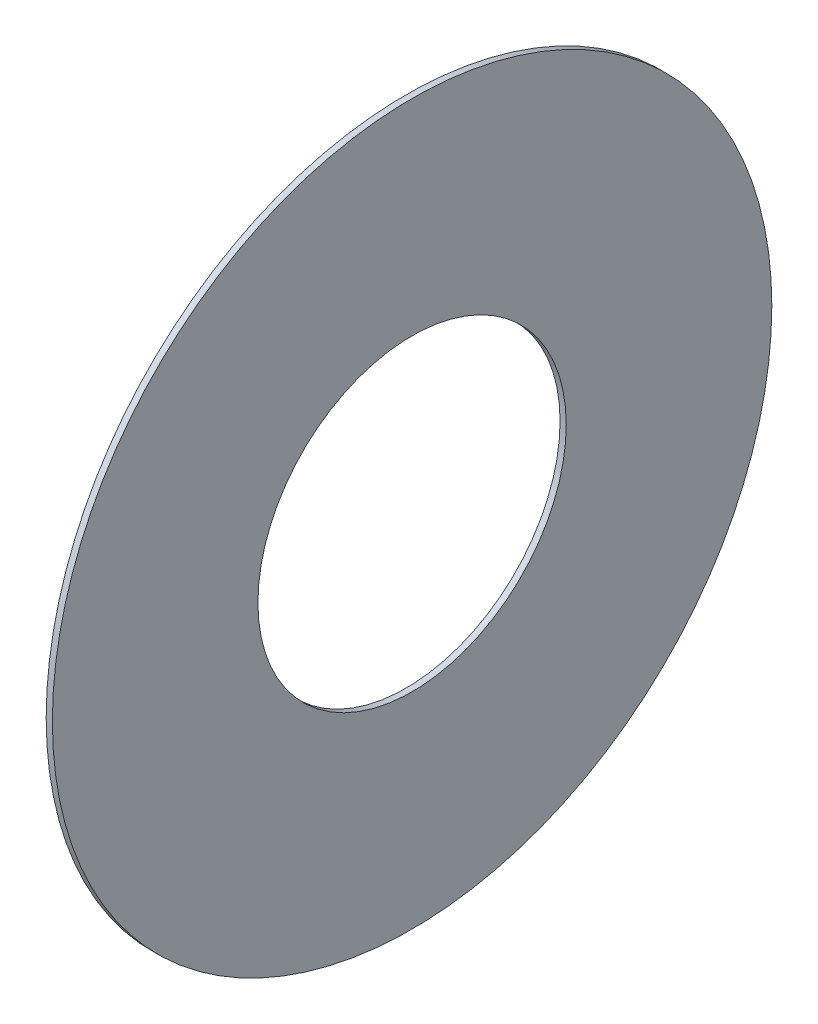
SolidWorks part; units mm, degrees
ref_plane "Front Plane" through (0, 0, 0) normal (0, 0, 1) x (1, 0, 0)
ref_plane "Top Plane" through (0, 0, 0) normal (0, 1, 0) x (1, 0, 0)
ref_plane "Right Plane" through (0, 0, 0) normal (1, 0, 0) x (0, 0, -1)
sketch "Sketch1" plane through (0, 0, 0) normal (1, 0, 0) x (0, 0, -1)
  circle A0 centre (0, 0) radius 48.895
  circle A1 centre (0, 0) radius 20.955
  dimension "D1" = 97.79
  dimension "D2" = 41.91
extrude "Boss-Extrude1" add sketch "Sketch1" along normal blind 0.8382
